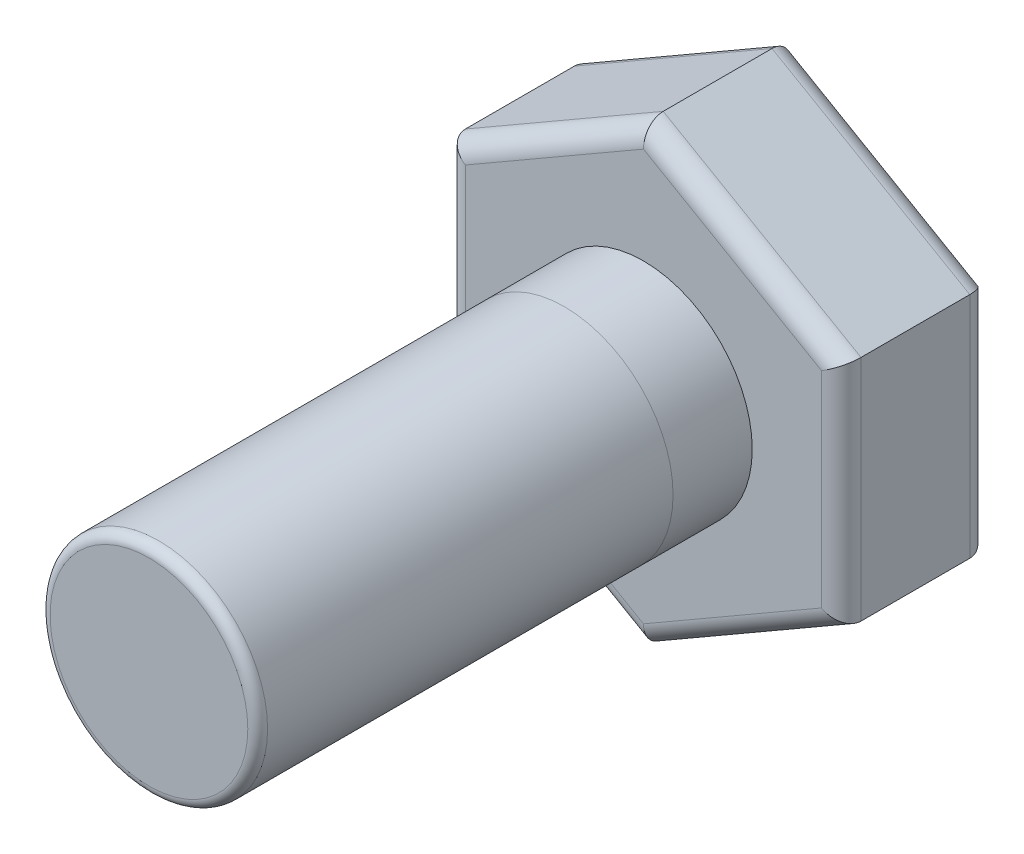
SolidWorks part; units mm, degrees
ref_plane "前视" through (0, 0, 0) normal (0, 0, 1) x (1, 0, 0)
ref_plane "上视" through (0, 0, 0) normal (0, 1, 0) x (1, 0, 0)
ref_plane "右视" through (0, 0, 0) normal (1, 0, 0) x (0, 0, -1)
sketch "草图1" plane through (0, 0, 0) normal (0, 0, 1) x (1, 0, 0)
  line L1 (20, 11.547) -> (0, 23.094)
  line L2 (0, 23.094) -> (-20, 11.547)
  line L3 (-20, 11.547) -> (-20, -11.547)
  line L4 (-20, -11.547) -> (0, -23.094)
  line L5 (0, -23.094) -> (20, -11.547)
  line L6 (20, -11.547) -> (20, 11.547)
  circle A0 centre (0, 0) radius 20 construction
  dimension "D1" = 40
extrude "基体-拉伸" add sketch "草图1" along normal blind 15
sketch "草图2" plane through (0, 0, 15) normal (0, 0, 1) x (1, 0, 0)
  circle A0 centre (0, 0) radius 11
  dimension "D1" = 22
extrude "凸台-拉伸1" add sketch "草图2" along normal blind 8
fillet "圆角3" radius 2 12 edges at (-10, 17.3205, 15) (-20, 0, 15) (-10, -17.3205, 15) (10, -17.3205, 15) (20, 0, 15) (10, -17.3205, 0) (-10, -17.3205, 0) (-20, 0, 0) (10, 17.3205, 15) (-10, 17.3205, 0) (10, 17.3205, 0) (20, 0, 0)
sketch "草图3" plane through (0, 0, 23) normal (0, 0, 1) x (1, 0, 0)
  circle A0 centre (0, 0) radius 10.995
  dimension "D1" = 21.99
extrude "拉伸1" add sketch "草图3" along normal blind 42
fillet "圆角4" radius 1 1 edges at (10.995, 0, 65)
